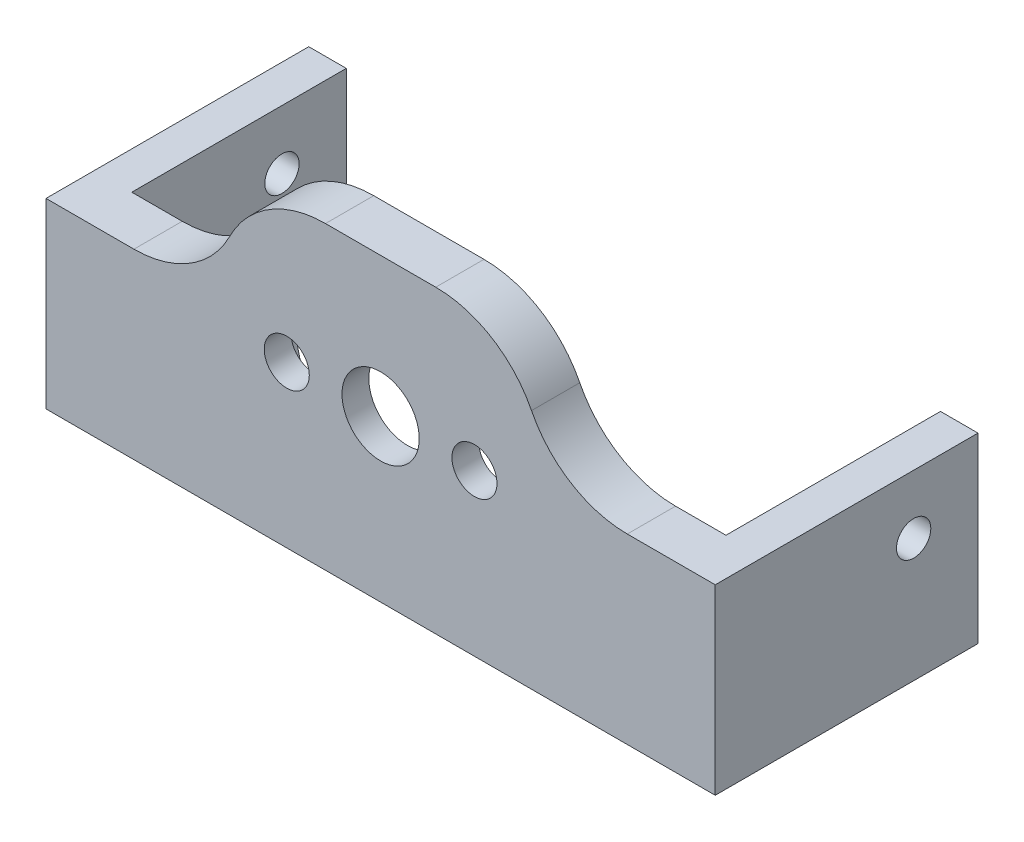
SolidWorks part; units mm, degrees
ref_plane "Front Plane" through (0, 0, 0) normal (0, 0, 1) x (1, 0, 0)
ref_plane "Top Plane" through (0, 0, 0) normal (0, 1, 0) x (1, 0, 0)
ref_plane "Right Plane" through (0, 0, 0) normal (1, 0, 0) x (0, 0, -1)
sketch "Sketch3" plane through (0, 0, 0) normal (0, 0, 1) x (1, 0, 0)
  line L0 (5.8713, 13.1422) -> (5.8713, -14.8578) construction
  line L1 (-7.1287, 13.1422) -> (18.8713, 13.1422)
  line L2 (-25.3287, 2.1422) -> (-25.3287, -14.8578)
  line L3 (-25.3287, -14.8578) -> (37.0713, -14.8578)
  line L4 (37.0713, 2.1422) -> (37.0713, -14.8578)
  line L5 (-7.1287, 13.1422) -> (-7.1287, 2.1422)
  line L6 (-7.1287, 2.1422) -> (-25.3287, 2.1422)
  line L7 (18.8713, 2.1422) -> (37.0713, 2.1422)
  line L8 (18.8713, 13.1422) -> (18.8713, 2.1422)
  dimension "D1" = 28
  dimension "D2" = 62.4
  dimension "D3" = 13
  dimension "D4" = 17
extrude "Boss-Extrude1" add sketch "Sketch3" along normal blind 4.5
sketch "Sketch4" plane through (0, 0, 0) normal (0, 0, -1) x (-1, 0, 0)
  line L0 (-18.8713, 13.1422) -> (7.1287, 13.1422) construction
  line L1 (25.3287, 2.1422) -> (25.3287, -14.8578) construction
  circle A0 centre (-5.8713, 0.1422) radius 12.55
  dimension "D1" = 25.1
  dimension "D3" = 31.2
  dimension "D2" = 13
extrude "Cut-Extrude1" cut sketch "Sketch4" against normal blind 2
sketch "Sketch5" plane through (0, 0, 2) normal (0, 0, -1) x (-1, 0, 0)
  line L0 (-5.8713, 12.511) -> (-5.8713, 0.1422) construction
  line L1 (-18.8713, 13.1422) -> (7.1287, 13.1422) construction
  circle A0 centre (-14.6213, 0.1422) radius 2.1
  circle A1 centre (2.8787, 0.1422) radius 2.1
  circle A2 centre (-5.8713, 0.1422) radius 3.6
  dimension "D1" = 17.5
  dimension "D2" = 4.2
  dimension "D3" = 7.2
  dimension "D4" = 13
extrude "Cut-Extrude2" cut sketch "Sketch5" against normal up to next
sketch "Sketch8" plane through (0, 0, 0) normal (0, 0, -1) x (-1, 0, 0)
  line L0 (25.3287, -14.8578) -> (-37.0713, -14.8578) construction
  line L1 (-37.0713, 2.1422) -> (-33.5713, 2.1422)
  line L2 (-37.0713, 2.1422) -> (-37.0713, -14.8578)
  line L3 (-37.0713, -14.8578) -> (-33.5713, -14.8578)
  line L4 (-33.5713, 2.1422) -> (-33.5713, -14.8578)
  line L5 (-5.8713, 13.1422) -> (-5.8713, -21.1015) construction
  line L6 (-18.8713, 13.1422) -> (7.1287, 13.1422) construction
  line L7 (25.3287, -14.8578) -> (21.8287, -14.8578)
  line L8 (21.8287, 2.1422) -> (21.8287, -14.8578)
  line L9 (25.3287, 2.1422) -> (21.8287, 2.1422)
  line L10 (25.3287, 2.1422) -> (25.3287, -14.8578)
  dimension "D1" = 3.5
extrude "Boss-Extrude3" add sketch "Sketch8" along normal blind 20
fillet "Fillet3" radius 10 2 edges at (-7.1287, 2.1422, 2.25) (18.8713, 2.1422, 2.25)
fillet "Fillet4" radius 10 2 edges at (-7.1287, 13.1422, 2.25) (18.8713, 13.1422, 2.25)
sketch "Sketch9" plane through (37.0713, 0, 0) normal (1, 0, 0) x (0, 0, -1)
  line L0 (-4.5, -14.8578) -> (20, -14.8578) construction
  line L1 (20, 2.1422) -> (20, -14.8578) construction
  circle A0 centre (14, -3.3578) radius 1.6
  dimension "D1" = 3.2
  dimension "D2" = 11.5
  dimension "D3" = 6
extrude "Cut-Extrude3" cut sketch "Sketch9" against normal through all
